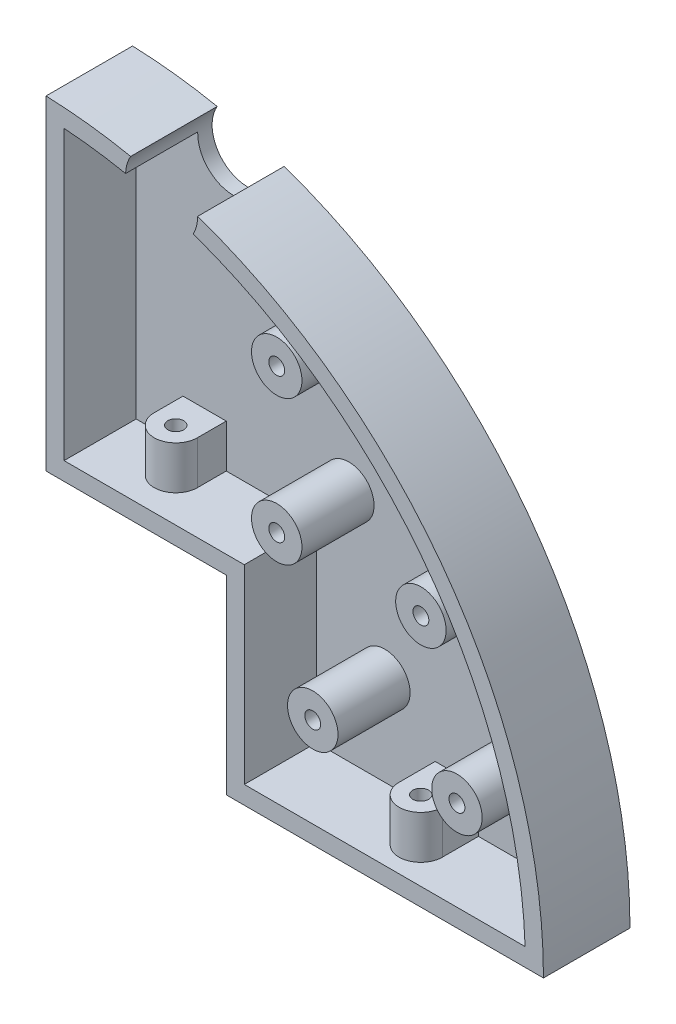
SolidWorks part; units mm, degrees
material "PET"
ref_plane "Front Plane" through (0, 0, 0) normal (0, 0, 1) x (1, 0, 0)
ref_plane "Top Plane" through (0, 0, 0) normal (0, 1, 0) x (1, 0, 0)
ref_plane "Right Plane" through (0, 0, 0) normal (1, 0, 0) x (0, 0, -1)
sketch "Sketch1" plane through (0, 0, 0) normal (0, 0, 1) x (1, 0, 0)
  line L0 (0, 33.528) -> (0, 90.805) construction
  line L1 (-34.925, -33.528) -> (34.925, -33.528) construction
  line L2 (-34.925, -33.528) -> (-34.925, 33.528) construction
  line L3 (-34.925, 33.528) -> (34.925, 33.528) construction
  line L4 (34.925, -33.528) -> (34.925, 33.528) construction
  line L5 (-34.925, -33.528) -> (34.925, 33.528) construction
  line L6 (-34.925, 33.528) -> (34.925, -33.528) construction
  line L7 (3.175, 33.528) -> (3.175, 90.7495) construction
  line L8 (34.925, 0) -> (90.805, 0) construction
  line L9 (41.4443, 30.5048) -> (38.608, 34.544)
  line L10 (87.122, -34.544) -> (38.608, -34.544)
  line L11 (87.122, -34.544) -> (87.122, 34.544)
  line L12 (87.122, 34.544) -> (38.608, 34.544)
  line L13 (38.608, -34.544) -> (38.608, 34.544)
  line L14 (87.122, -34.544) -> (38.608, 34.544) construction
  line L15 (87.122, 34.544) -> (38.608, -34.544) construction
  line L16 (87.122, -34.544) -> (84.2857, -30.5048)
  circle A0 centre (0, 0) radius 90.805 construction
  circle A1 centre (41.4443, 30.5048) radius 1.5875
  circle A2 centre (84.2857, -30.5048) radius 1.5875
  point P13 (62.865, 0)
  point P22 (62.0063, 7.8204)
  point P23 (62.865, 0)
  dimension "D1" = 181.61
  dimension "D7" = 3.175
  dimension "D2" = 67.056
  dimension "D3" = 69.85
  dimension "D4" = 3.175
  dimension "D5" = 69.088
  dimension "D6" = 48.514
  dimension "D8" = 74.549
sketch "Sketch2" plane through (0, 0, 0) normal (0, 0, 1) x (1, 0, 0)
  line L0 (34.925, 0) -> (90.805, 0)
  line L1 (34.925, 0) -> (34.925, 33.528)
  line L2 (34.925, 33.528) -> (3.175, 33.528)
  line L3 (3.175, 33.528) -> (3.175, 90.7495)
  arc A0 (90.805, 0) -> (3.175, 90.7495) centre (0, 0) ccw
  point P7 (3.4685, 33.528)
  point P12 (3.175, 90.7495)
extrude "Boss-Extrude1" add sketch "Sketch2" along normal blind 2.54
sketch "Sketch3" plane through (0, 0, 2.54) normal (0, 0, 1) x (1, 0, 0)
  line L0 (6.35, 36.703) -> (38.1, 36.703)
  line L1 (38.1, 36.703) -> (38.1, 3.175)
  line L2 (38.1, 3.175) -> (87.5725, 3.175)
  line L3 (34.925, 0) -> (90.805, 0) construction
  line L4 (34.925, 33.528) -> (34.925, 0)
  line L5 (34.925, 0) -> (90.805, 0)
  line L6 (3.175, 90.7495) -> (3.175, 33.528)
  line L7 (3.175, 33.528) -> (34.925, 33.528)
  line L8 (34.925, 33.528) -> (34.925, 0)
  line L9 (34.925, 0) -> (90.805, 0)
  line L10 (3.175, 90.7495) -> (3.175, 33.528)
  line L11 (3.175, 33.528) -> (34.925, 33.528)
  line L12 (6.35, 36.703) -> (6.35, 87.3996)
  arc A0 (6.35, 87.3996) -> (87.5725, 3.175) centre (0, 0) cw
  arc A1 (90.805, 0) -> (3.175, 90.7495) centre (0, 0) ccw
  arc A2 (90.805, 0) -> (3.175, 90.7495) centre (0, 0) ccw
  point P14 (0, 0)
  dimension "D6" = 3.175
  dimension "D2" = 3.175
  dimension "D3" = 3.175
  dimension "D4" = 3.175
  dimension "D5" = 3.175
  dimension "D1" = 0
extrude "Boss-Extrude2" add sketch "Sketch3" along normal blind 12.7
sketch "Sketch4" plane through (0, 36.703, 0) normal (0, 1, 0) x (1, 0, 0)
  line L1 (3.175, -7.62) -> (18.415, -7.62) construction
  line L2 (3.175, -15.24) -> (3.175, 0) construction
  line L3 (14.605, -7.62) -> (14.605, 0)
  line L4 (-34.925, 0) -> (34.925, 0) construction
  line L5 (14.605, 0) -> (22.225, 0)
  line L6 (22.225, 0) -> (22.225, -7.62)
  arc A0 (14.605, -7.62) -> (22.225, -7.62) centre (18.415, -7.62) ccw
  dimension "D2" = 7.62
  dimension "D1" = 15.24
extrude "Boss-Extrude3" add sketch "Sketch4" along normal blind 7.62
sketch "Sketch5" plane through (0, 44.323, 0) normal (0, 1, 0) x (1, 0, 0)
  circle A0 centre (18.415, -7.62) radius 1.397
  arc A1 (14.605, -7.62) -> (22.225, -7.62) centre (18.415, -7.62) ccw construction
  dimension "D1" = 2.794
extrude "Cut-Extrude1" cut sketch "Sketch5" against normal through all
sketch "Sketch6" plane through (0, 0, 2.54) normal (0, 0, 1) x (1, 0, 0)
  line L0 (50.165, 19.05) -> (75.565, 19.05) construction
  line L1 (43.815, 44.45) -> (43.815, 69.85) construction
  line L2 (62.865, 19.05) -> (62.865, 0) construction
  line L3 (43.815, 44.45) -> (69.215, 44.45) construction
  circle A0 centre (43.815, 44.45) radius 4.445
  circle A1 centre (43.815, 69.85) radius 4.445
  circle A2 centre (50.165, 19.05) radius 4.445
  circle A3 centre (75.565, 19.05) radius 4.445
  circle A4 centre (69.215, 44.45) radius 4.445
  dimension "D1" = 8.89
  dimension "D2" = 25.4
  dimension "D3" = 25.4
  dimension "D4" = 6.35
  dimension "D5" = 19.05
  dimension "D6" = 25.4
  dimension "D7" = 25.4
extrude "Boss-Extrude4" add sketch "Sketch6" along normal up to surface (12.7 mm away) up to face at (37.0673, 35.1014, 15.24)
sketch "Sketch7" plane through (0, 0, 15.24) normal (0, 0, 1) x (1, 0, 0)
  line L1 (23.5408, 85.7266) -> (0, 0) construction
  circle A0 centre (23.5408, 85.7266) radius 6.35
  dimension "D4" = 12.7
  dimension "D2" = 17.272
  dimension "D3" = 88.9
extrude "Cut-Extrude2" cut sketch "Sketch7" against normal through all contours A0
sketch "Sketch8" plane through (0, 0, 15.24) normal (0, 0, 1) x (1, 0, 0)
  circle A0 centre (43.815, 69.85) radius 1.397
  circle A1 centre (43.815, 44.45) radius 1.397
  circle A2 centre (69.215, 44.45) radius 1.397
  circle A3 centre (75.565, 19.05) radius 1.397
  circle A4 centre (50.165, 19.05) radius 1.397
  dimension "D1" = 2.794
extrude "Cut-Extrude3" cut sketch "Sketch8" against normal through all
sketch "Sketch9" plane through (0, 3.175, 0) normal (0, 1, 0) x (1, 0, 0)
  line L0 (62.8362, -15.24) -> (62.8362, -8.89) construction
  line L1 (38.1, -15.24) -> (87.5725, -15.24) construction
  line L2 (66.6462, -8.89) -> (66.6462, -2.54)
  line L3 (38.1, -2.54) -> (87.5725, -2.54) construction
  line L4 (66.6462, -2.54) -> (59.0262, -2.54)
  line L5 (59.0262, -2.54) -> (59.0262, -8.89)
  line L6 (62.8362, -8.89) -> (62.8362, -2.54) construction
  arc A0 (59.0262, -8.89) -> (66.6462, -8.89) centre (62.8362, -8.89) ccw
  dimension "D1" = 7.62
extrude "Boss-Extrude5" add sketch "Sketch9" along normal blind 7.62 contours A0 L2 L4 L5
sketch "Sketch10" plane through (0, 10.795, 0) normal (0, 1, 0) x (1, 0, 0)
  circle A0 centre (62.8362, -8.89) radius 1.397
  arc A1 (59.0262, -8.89) -> (66.6462, -8.89) centre (62.8362, -8.89) ccw construction
  dimension "D1" = 2.794
extrude "Cut-Extrude4" cut sketch "Sketch10" against normal through all
